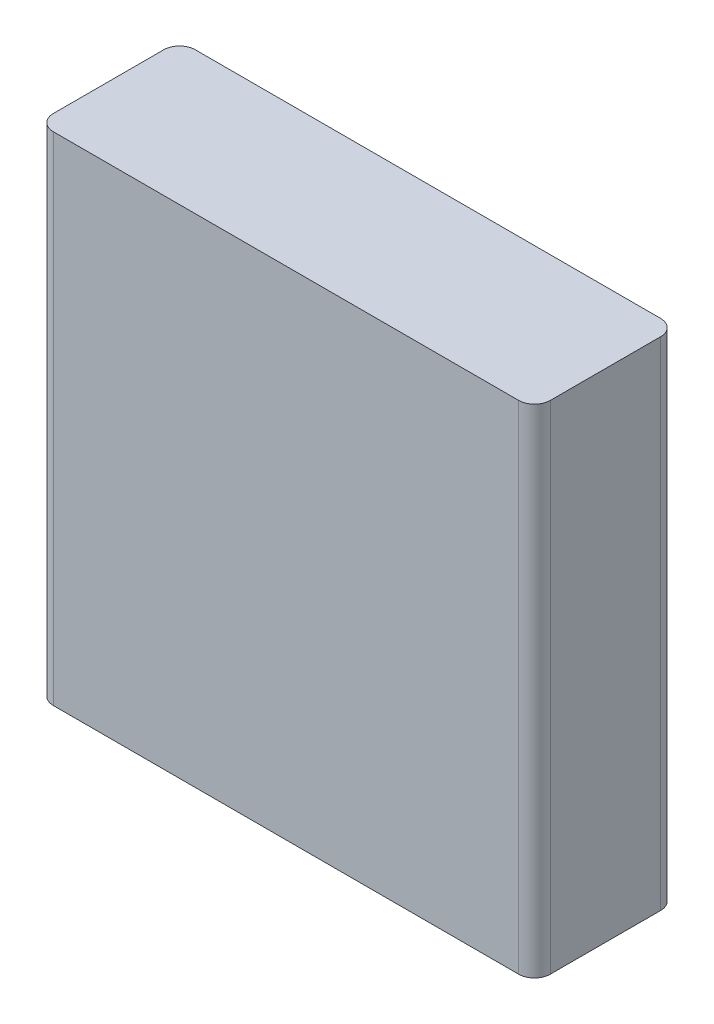
SolidWorks part; units mm, degrees
ref_plane "前视基准面" through (0, 0, 0) normal (0, 0, 1) x (1, 0, 0)
ref_plane "上视基准面" through (0, 0, 0) normal (0, 1, 0) x (1, 0, 0)
ref_plane "右视基准面" through (0, 0, 0) normal (1, 0, 0) x (0, 0, -1)
other "Configuration Table"
sketch "草图1" plane through (0, 0, 0) normal (0, 0, 1) x (1, 0, 0)
  line L0 (0, 0) -> (63, 0)
  line L1 (63, 0) -> (63, 63)
  line L2 (63, 63) -> (0, 63)
  line L3 (0, 63) -> (0, 0)
  dimension "width" = 63
  dimension "height" = 63
extrude "BlockExtrude" add sketch "草图1" along normal blind 18
fillet "Fillet" radius 2 4 edges at (0, 31.5, 0) (63, 31.5, 0) (0, 31.5, 18) (63, 31.5, 18)
